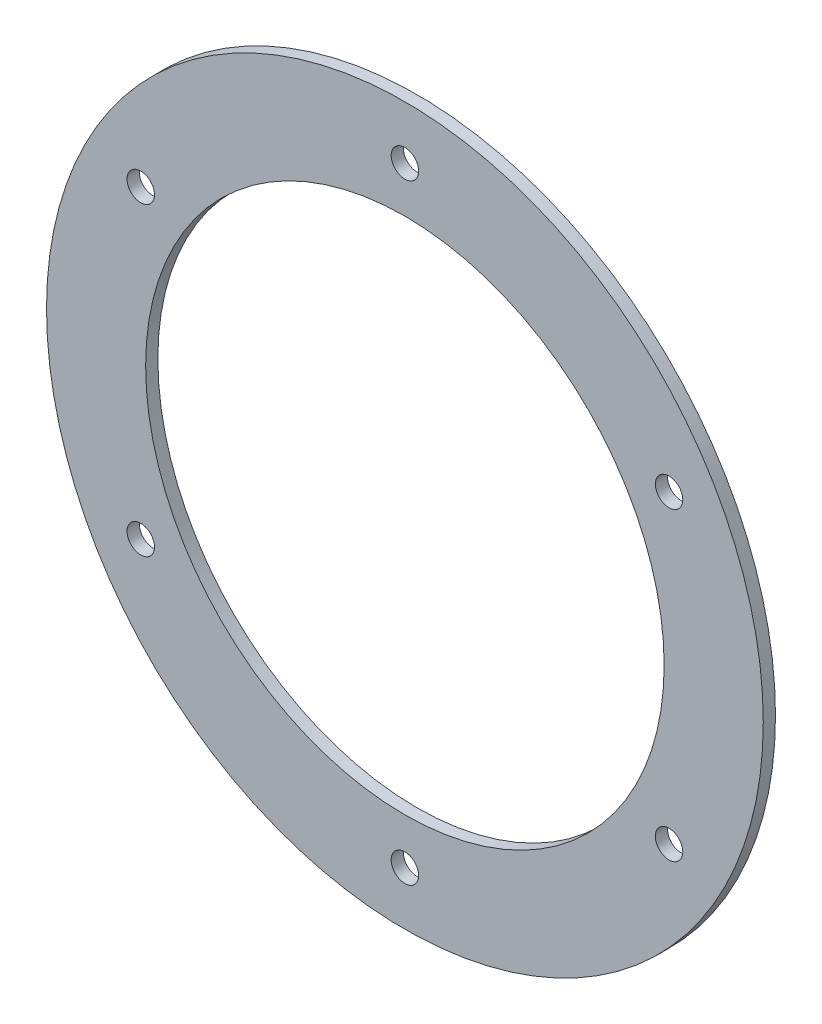
SolidWorks part; units mm, degrees
ref_plane "前视" through (0, 0, 0) normal (0, 0, 1) x (1, 0, 0)
ref_plane "上视" through (0, 0, 0) normal (0, 1, 0) x (1, 0, 0)
ref_plane "右视" through (0, 0, 0) normal (1, 0, 0) x (0, 0, -1)
sketch "草图1" plane through (0, 0, 0) normal (0, 0, 1) x (1, 0, 0)
  circle A0 centre (0, 0) radius 117.5
  circle A1 centre (0, 0) radius 85
  circle A2 centre (0, 0) radius 100 construction
  circle A3 centre (0, 100) radius 4.5
  circle A4 centre (86.6025, 50) radius 4.5
  circle A5 centre (86.6025, -50) radius 4.5
  circle A6 centre (0, -100) radius 4.5
  circle A7 centre (-86.6025, -50) radius 4.5
  circle A8 centre (-86.6025, 50) radius 4.5
  dimension "D1" = 235
  dimension "D2" = 200
  dimension "D3" = 170
  dimension "D4" = 9
  dimension "D5" = 6
extrude "凸台-拉伸1" add sketch "草图1" along normal blind 4
scale "缩放比例1" scale about centroid uniform scaling yes scale factor 0.2
